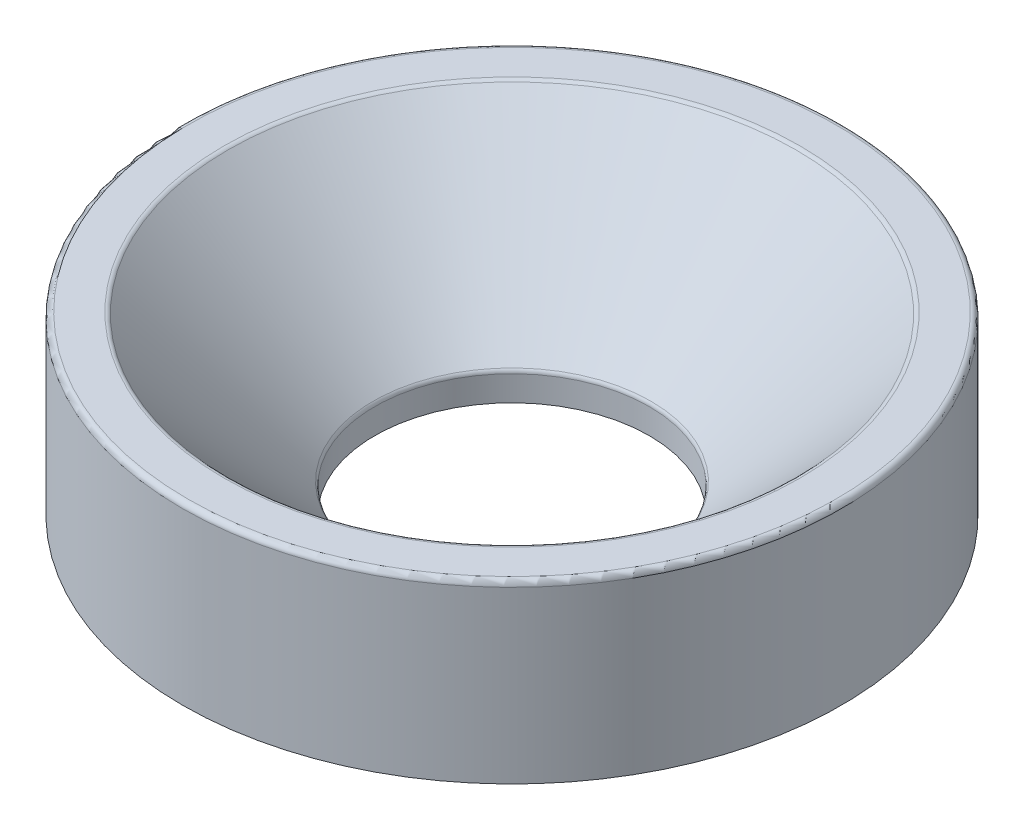
SolidWorks part; units mm, degrees
ref_plane "前视基准面" through (0, 0, 0) normal (0, 0, 1) x (1, 0, 0)
ref_plane "上视基准面" through (0, 0, 0) normal (0, 1, 0) x (1, 0, 0)
ref_plane "右视基准面" through (0, 0, 0) normal (1, 0, 0) x (0, 0, -1)
sketch "草图1" plane through (0, 0, 0) normal (0, 1, 0) x (1, 0, 0)
  circle A0 centre (0, 0) radius 6
  circle A1 centre (0, 0) radius 2.5
  dimension "D1" = 12
  dimension "D2" = 5
extrude "凸台-拉伸1" add sketch "草图1" along normal blind 3.2
chamfer "倒角1" distance 2.7 angle 45 1 edges at (0, 3.2, 2.5)
fillet "圆角1" radius 0.1 3 edges at (0, 3.2, 6) (0, 3.2, 5.2) (0, 0.5, 2.5)
